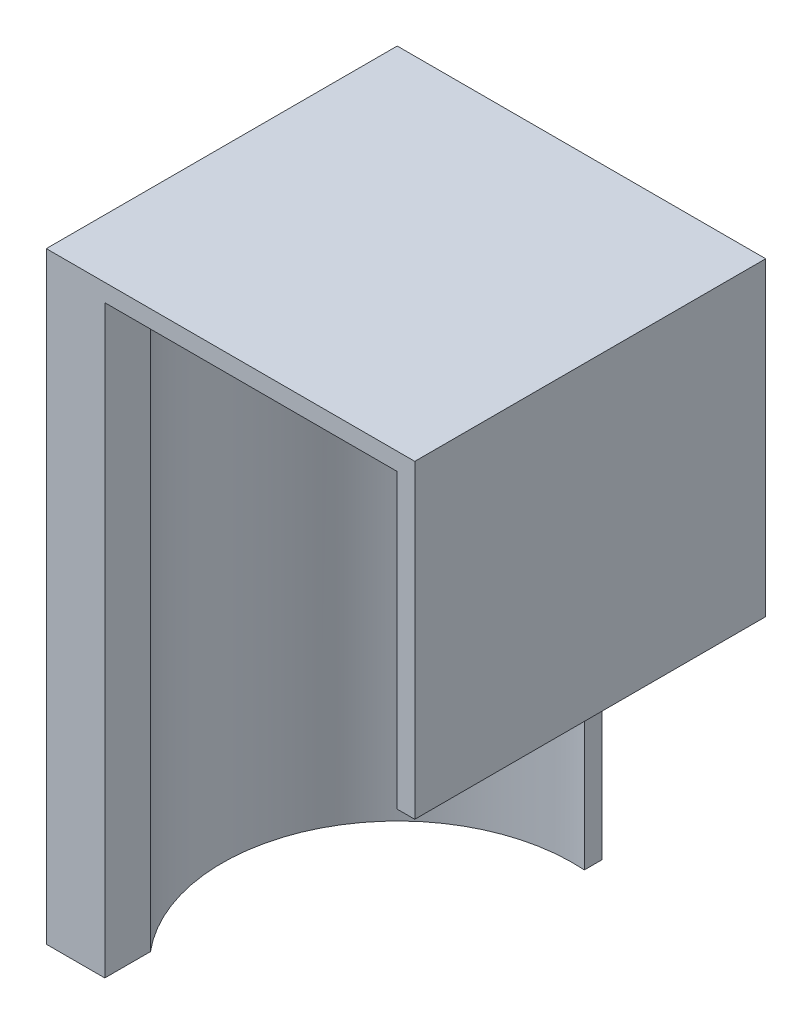
SolidWorks part; units mm, degrees
ref_plane "Front Plane" through (0, 0, 0) normal (0, 0, 1) x (1, 0, 0)
ref_plane "Top Plane" through (0, 0, 0) normal (0, 1, 0) x (1, 0, 0)
ref_plane "Right Plane" through (0, 0, 0) normal (1, 0, 0) x (0, 0, -1)
sketch "Sketch1" plane through (0, 0, 0) normal (1, 0, 0) x (0, 0, -1)
  line L1 (30, 50) -> (-30, 50)
  line L2 (30, 50) -> (30, -50)
  line L3 (30, -50) -> (-30, -50)
  line L4 (-30, 50) -> (-30, -50)
  line L5 (30, 50) -> (-30, -50) construction
  line L6 (30, -50) -> (-30, 50) construction
  point P0 (0, 0)
  dimension "D1" = 100
  dimension "D2" = 60
extrude "Boss-Extrude1" add sketch "Sketch1" along normal blind 3
sketch "Sketch2" plane through (3, 0, 0) normal (1, 0, 0) x (0, 0, -1)
  line L1 (30, 50) -> (27, 50)
  line L2 (30, 50) -> (30, 0)
  line L3 (30, 0) -> (27, 0)
  line L4 (27, 50) -> (27, 0)
  dimension "D1" = 3
extrude "Boss-Extrude2" add sketch "Sketch2" along normal blind 60
sketch "Sketch3" plane through (0, 0, -27) normal (0, 0, 1) x (1, 0, 0)
  line L0 (63, 0) -> (3, 0) construction
  line L1 (63, 50) -> (60, 50)
  line L2 (63, 50) -> (63, 0)
  line L3 (63, 0) -> (60, 0)
  line L4 (60, 50) -> (60, 0)
  dimension "D1" = 3
extrude "Boss-Extrude3" add sketch "Sketch3" along normal up to surface (57 mm away) up to face at (1.5, 0, 30)
sketch "Sketch4" plane through (0, 50, 0) normal (0, 1, 0) x (1, 0, 0)
  line L1 (63, 30) -> (0, 30)
  line L2 (63, 30) -> (63, -30)
  line L3 (63, -30) -> (0, -30)
  line L4 (0, 30) -> (0, -30)
extrude "Boss-Extrude4" add sketch "Sketch4" along normal blind 3
sketch "Sketch7" plane through (0, 50, 0) normal (0, -1, 0) x (1, 0, 0)
  line L1 (0, -30) -> (35, -30)
  line L2 (63, -30) -> (3, -30) construction
  line L3 (35, -30) -> (35, -27)
  line L4 (60, -27) -> (3, -27) construction
  line L5 (0, 30) -> (10, 30)
  line L6 (3, 30) -> (60, 30) construction
  line L7 (10, 30) -> (10, 22.1946)
  line L8 (0, 30) -> (0, -30)
  line L9 (3, -27) -> (3, 30) construction
  arc A1 (35, -27) -> (10, 22.1946) centre (33, 2.9333) cw
  point P1 (0, 0)
  point P19 (0, 0)
  point P20 (0.7983, -30)
  point P21 (0.4375, 30)
  dimension "D1" = 10
  dimension "D2" = 35
  dimension "D3" = 30
extrude "Boss-Extrude6" add sketch "Sketch7" along normal up to surface (100 mm away) up to face at (1.5, -50, 0)
